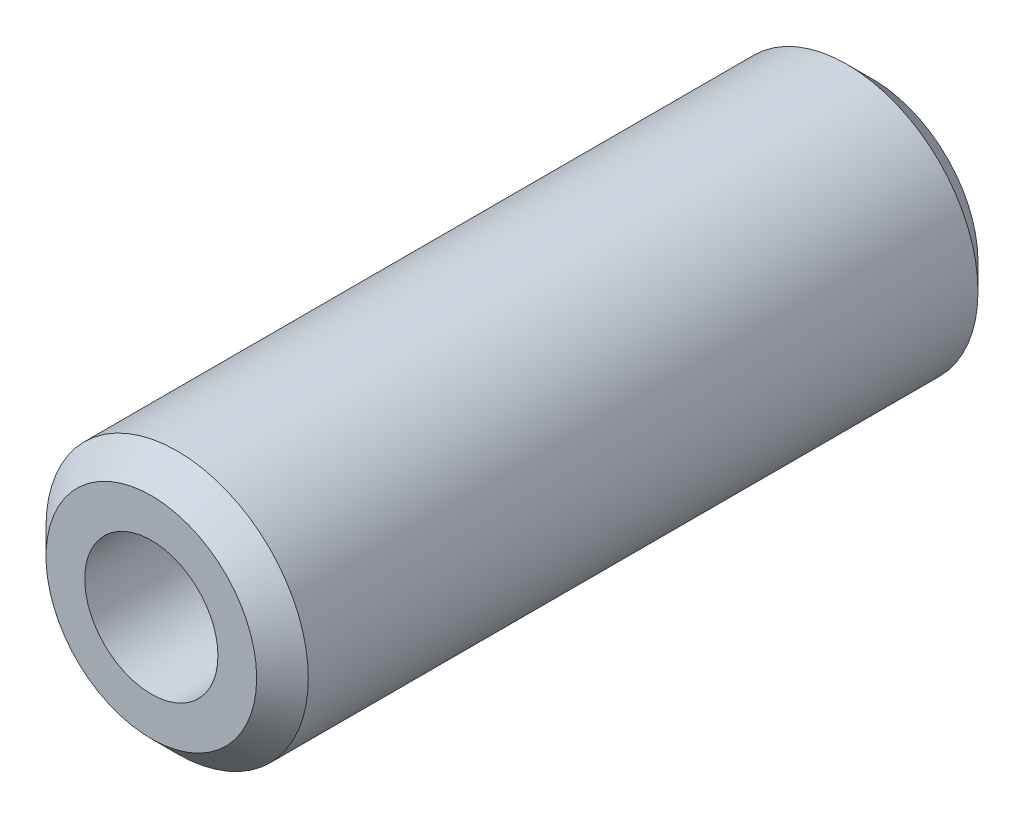
SolidWorks part; units mm, degrees
ref_plane "Front Plane" through (0, 0, 0) normal (0, 0, 1) x (1, 0, 0)
ref_plane "Top Plane" through (0, 0, 0) normal (0, 1, 0) x (1, 0, 0)
ref_plane "Right Plane" through (0, 0, 0) normal (1, 0, 0) x (0, 0, -1)
sketch "Sketch1" plane through (0, 0, 0) normal (0, 0, 1) x (1, 0, 0)
  circle A0 centre (0, 0) radius 12.7
  dimension "D1" = 25.4
extrude "Boss-Extrude1" add sketch "Sketch1" along normal blind 69.85
sketch "Sketch2" plane through (0, 0, 69.85) normal (0, 0, 1) x (1, 0, 0)
  circle A0 centre (0, 0) radius 6.45
  dimension "D1" = 12.9
extrude "Cut-Extrude1" cut sketch "Sketch2" against normal through all
chamfer "Chamfer1" distance 2.5 angle 45 2 edges at (12.7, 0, 69.85) (12.7, 0, 0)
